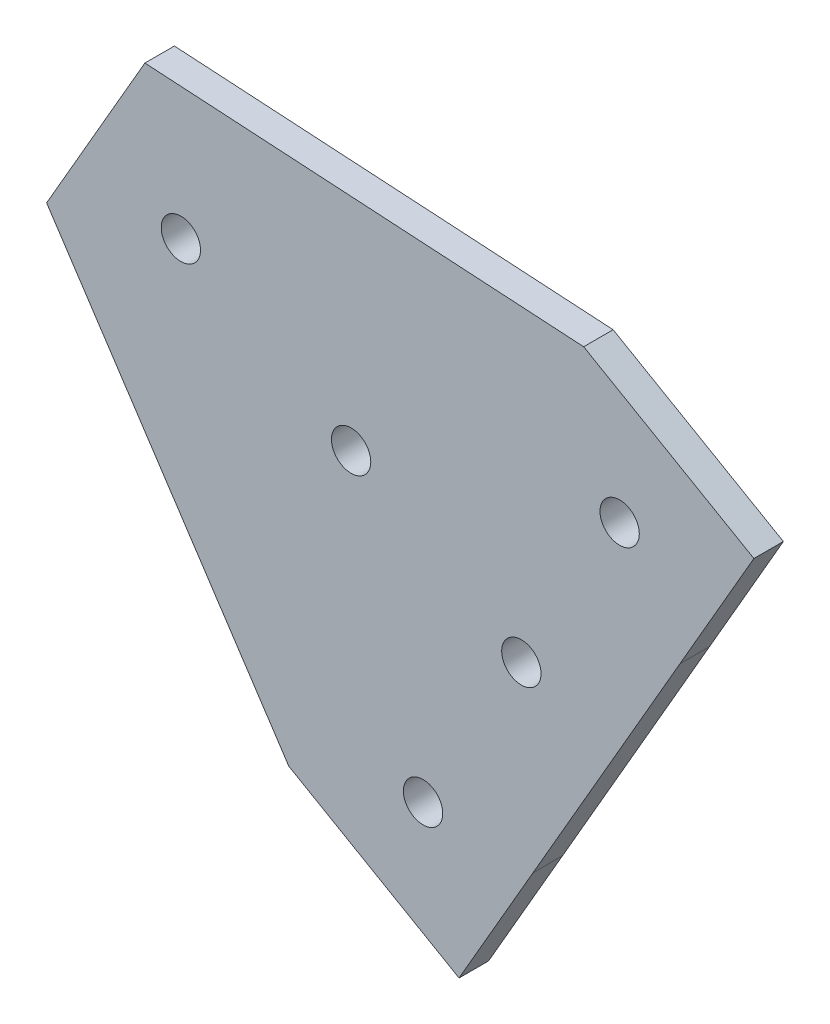
SolidWorks part; units mm, degrees
ref_plane "前视基准面" through (0, 0, 0) normal (0, 0, 1) x (1, 0, 0)
ref_plane "上视基准面" through (0, 0, 0) normal (0, 1, 0) x (1, 0, 0)
ref_plane "右视基准面" through (0, 0, 0) normal (1, 0, 0) x (0, 0, -1)
sketch "草图1" plane through (0, 0, 0) normal (0, 0, 1) x (1, 0, 0)
  line L0 (14.2636, -6.9795) -> (29.1705, 18.8401)
  line L1 (29.2163, 18.9211) -> (36.7163, 31.9115)
  line L2 (36.7163, 31.9115) -> (19.3958, 41.9115)
  line L3 (19.3958, 41.9115) -> (-25.2452, 44.591)
  line L4 (-25.2452, 44.591) -> (-35.2452, 27.2705)
  line L5 (-35.2452, 27.2705) -> (-10.6042, -10.05)
  line L6 (-10.6042, -10.05) -> (6.7163, -20.05)
  line L7 (6.7163, -20.05) -> (14.2163, -7.0597)
  circle A0 centre (-21.585, 30.9307) radius 2
  circle A1 centre (3.056, -6.3898) radius 2
  arc A2 (14.2636, -6.9795) -> (14.2163, -7.0597) centre (18.5464, -9.5597) ccw
  arc A3 (29.2163, 18.9211) -> (29.1705, 18.8401) centre (33.5464, 16.4211) ccw
  circle A4 centre (13.056, 10.9307) radius 2
  circle A5 centre (23.056, 28.2512) radius 2
  circle A6 centre (-4.2645, 20.9307) radius 2
extrude "凸台-拉伸1" add sketch "草图1" along normal blind 3
